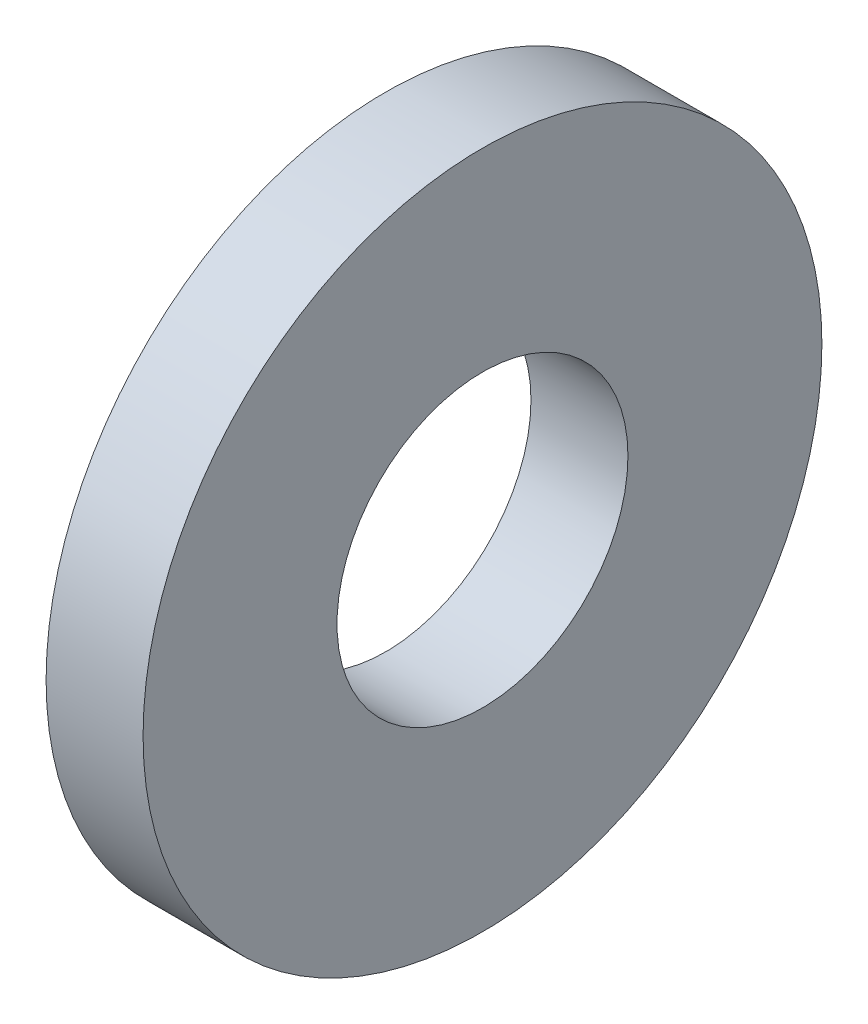
SolidWorks part; units mm, degrees
material "Nylon 101"
ref_plane "Front Plane" through (0, 0, 0) normal (0, 0, 1) x (1, 0, 0)
ref_plane "Top Plane" through (0, 0, 0) normal (0, 1, 0) x (1, 0, 0)
ref_plane "Right Plane" through (0, 0, 0) normal (1, 0, 0) x (0, 0, -1)
sketch "Sketch1" plane through (0, 0, 0) normal (1, 0, 0) x (0, 0, -1)
  circle A0 centre (0, 0) radius 11.1125
  circle A1 centre (0, 0) radius 4.7625
  dimension "D1" = 22.225
  dimension "D2" = 9.525
extrude "Boss-Extrude1" add sketch "Sketch1" along normal blind 3.175
